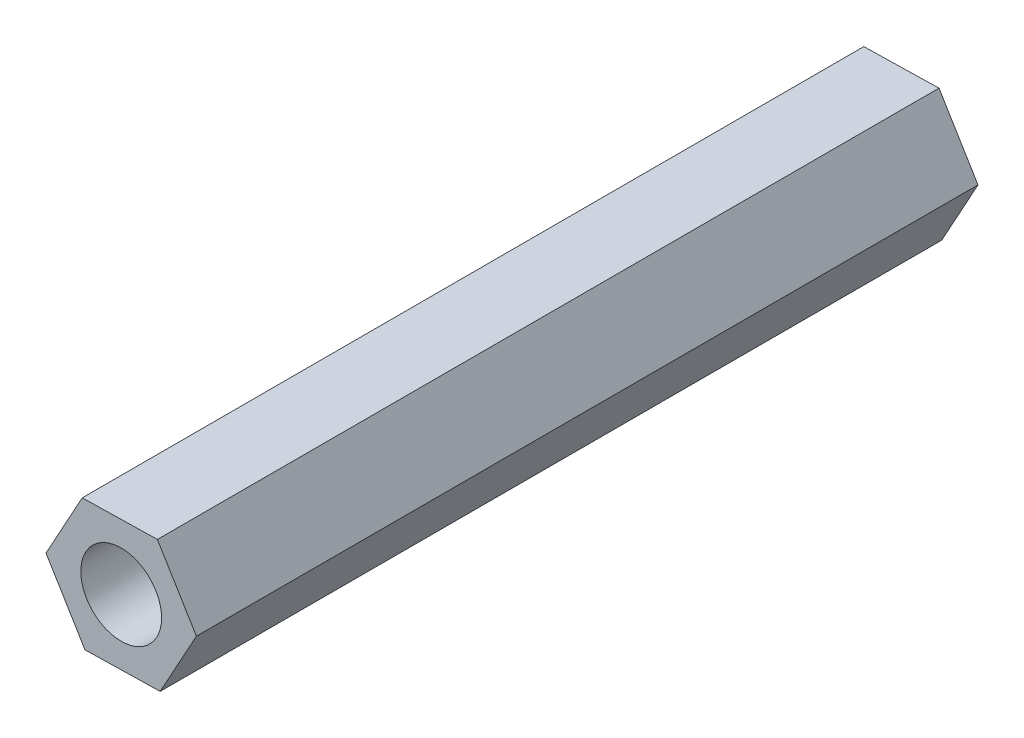
SolidWorks part; units mm, degrees
ref_plane "Front Plane" through (0, 0, 0) normal (0, 0, 1) x (1, 0, 0)
ref_plane "Top Plane" through (0, 0, 0) normal (0, 1, 0) x (1, 0, 0)
ref_plane "Right Plane" through (0, 0, 0) normal (1, 0, 0) x (0, 0, -1)
sketch "Sketch1" plane through (0, 0, 0) normal (0, 0, 1) x (1, 0, 0)
  line L1 (1.3898, 2.5302) -> (-1.4963, 2.4687)
  line L2 (-1.4963, 2.4687) -> (-2.8861, -0.0615)
  line L3 (-2.8861, -0.0615) -> (-1.3898, -2.5302)
  line L4 (-1.3898, -2.5302) -> (1.4963, -2.4687)
  line L5 (1.4963, -2.4687) -> (2.8861, 0.0615)
  line L6 (2.8861, 0.0615) -> (1.3898, 2.5302)
  circle A0 centre (0, 0) radius 2.5 construction
  circle A1 centre (0, 0) radius 1.55
  dimension "D1" = 5
  dimension "D2" = 3.1
extrude "Boss-Extrude1" add sketch "Sketch1" along normal blind 30
